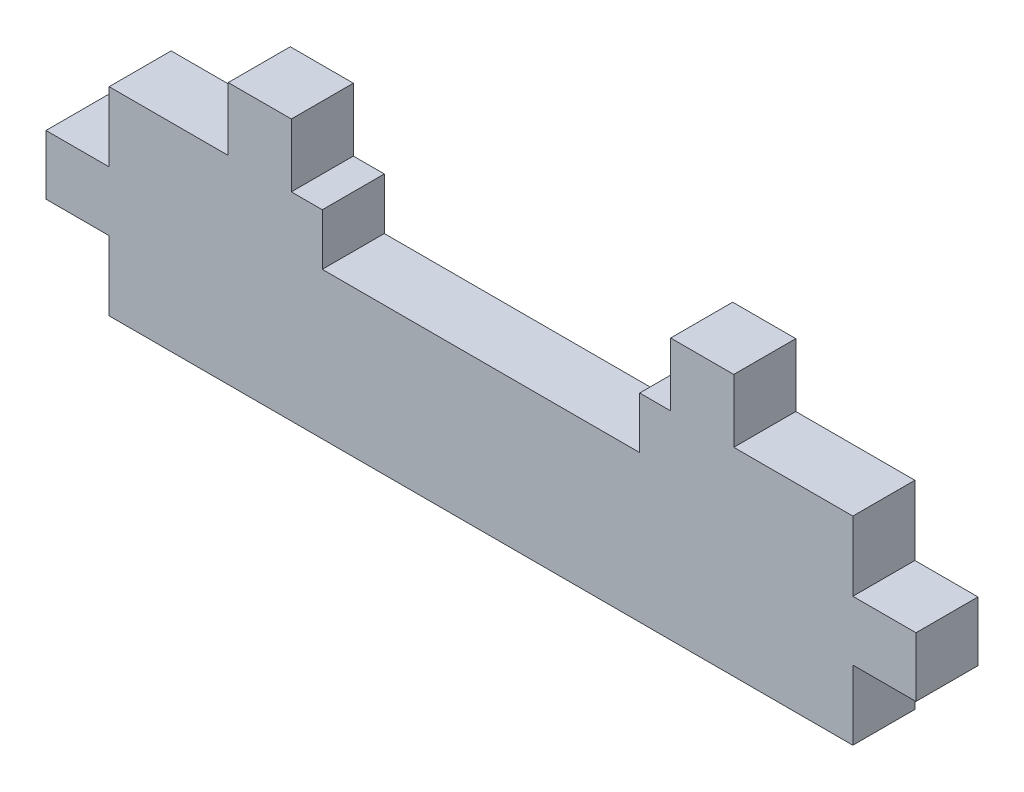
SolidWorks part; units mm, degrees
ref_plane "Front Plane" through (0, 0, 0) normal (0, 0, 1) x (1, 0, 0)
ref_plane "Top Plane" through (0, 0, 0) normal (0, 1, 0) x (1, 0, 0)
ref_plane "Right Plane" through (0, 0, 0) normal (1, 0, 0) x (0, 0, -1)
sketch "Sketch2" plane through (0, 0, 0) normal (0, 0, 1) x (1, 0, 0)
  line L0 (0, -6.59) -> (18.735, -6.59)
  line L1 (0, 6.59) -> (21.915, 6.59) construction
  line L2 (0, 6.59) -> (0, -6.59) construction
  line L3 (0, -6.59) -> (21.915, -6.59) construction
  line L4 (21.915, 6.59) -> (21.915, -6.59) construction
  line L5 (18.735, -6.59) -> (18.735, -3.09)
  line L6 (18.735, -3.09) -> (21.915, -3.09)
  line L7 (21.915, -3.09) -> (21.915, -0.09)
  line L8 (21.915, -0.09) -> (18.735, -0.09)
  line L9 (18.735, -0.09) -> (18.735, 3.41)
  line L10 (18.735, 3.41) -> (12.735, 3.41)
  line L11 (12.735, 3.41) -> (12.735, 6.59)
  line L12 (12.735, 6.59) -> (9.555, 6.59)
  line L13 (9.555, 6.59) -> (9.555, 3.41)
  line L14 (9.555, 3.41) -> (7.995, 3.41)
  line L15 (7.995, 3.41) -> (7.995, 0.81)
  line L16 (7.995, 0.81) -> (0.5693, 0.81)
  line L17 (0, -6.59) -> (0, 0.81)
  line L18 (0.5693, 0.81) -> (0, 0.81)
  point P0 (0, 0)
  point P6 (0, 0)
  dimension "D1" = 21.915
  dimension "D2" = 13.18
  dimension "D3" = 10.74
  dimension "D4" = 3.18
  dimension "D5" = 6
  dimension "D6" = 3
  dimension "D7" = 3.18
  dimension "D8" = 2.6
  dimension "D9" = 3.18
  dimension "D10" = 3.5
extrude "Boss-Extrude1" add sketch "Sketch2" along normal blind 3.125
mirror "Mirror1" about plane through (0, -6.59, 3.125) normal (1, 0, 0) of "Boss-Extrude1"
